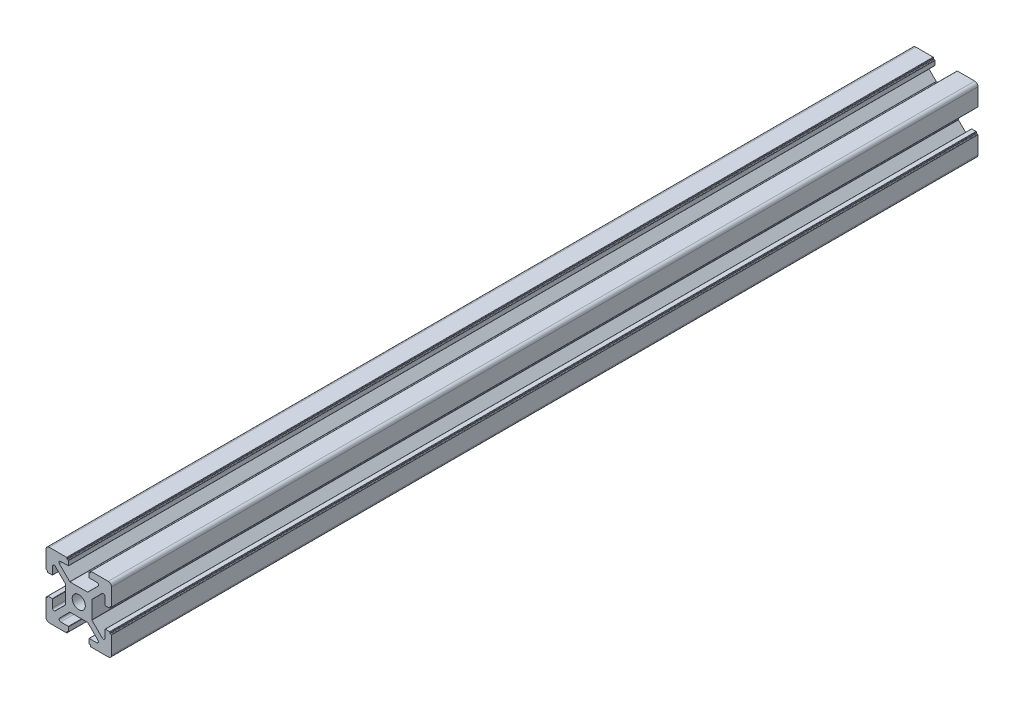
SolidWorks part; units mm, degrees
ref_plane "Plane1" through (0, 0, 0) normal (0, 0, 1) x (1, 0, 0)
ref_plane "Plane2" through (0, 0, 0) normal (0, 1, 0) x (1, 0, 0)
ref_plane "Plane3" through (0, 0, 0) normal (1, 0, 0) x (0, 0, -1)
sketch "Sketch1" plane through (0, 0, 0) normal (0, 0, 1) x (1, 0, 0)
  line L0 (-26.4662, 0) -> (25.1675, 0) construction
  line L1 (0, 16.7588) -> (0, -17.8201) construction
  line L2 (-10, 9) -> (-10, 3.7)
  line L3 (8, -5.5201) -> (8, -3.2)
  line L4 (-4, 0) -> (-4, 2.6858)
  line L5 (-2.6858, 4) -> (2.6858, 4)
  line L6 (4, 0) -> (4, 2.6858)
  line L7 (-4, -4) -> (4, 4) construction
  line L8 (-4, 4) -> (4, -4) construction
  line L9 (-9, 10) -> (-3.7, 10)
  line L10 (-8, 5.5201) -> (-8, 3.2)
  line L11 (10, -9) -> (10, -3.7)
  line L12 (9.6, -3.6) -> (9.9, -3.6)
  line L13 (-10, 10) -> (10, -10) construction
  line L14 (-10, -10) -> (10, 10) construction
  line L15 (9.5, -3.2) -> (9.5, -3.5)
  line L16 (8.1, -3.1) -> (9.4, -3.1)
  line L17 (-5.5201, 8) -> (-3.2, 8)
  line L18 (-7.1464, 5.8737) -> (-4.0293, 2.7565)
  line L19 (-5.8737, 7.1464) -> (-2.7565, 4.0293)
  line L20 (-3.1, 8.1) -> (-3.1, 9.4)
  line L21 (-3.2, 9.5) -> (-3.5, 9.5)
  line L22 (-3.6, 9.6) -> (-3.6, 9.9)
  line L23 (3.1, 8.1) -> (3.1, 9.4)
  line L24 (3.2, 9.5) -> (3.5, 9.5)
  line L25 (3.6, 9.6) -> (3.6, 9.9)
  line L26 (2.7565, 4.0293) -> (5.8737, 7.1464)
  line L27 (4.0293, 2.7565) -> (7.1464, 5.8737)
  line L28 (-8, 8) -> (8, 8) construction
  line L29 (-8, 8) -> (-8, -8) construction
  line L30 (8, 8) -> (8, -8) construction
  line L31 (3.7, 10) -> (9, 10)
  line L32 (-9, 10) -> (9, 10) construction
  line L33 (3.2, 8) -> (5.5201, 8)
  line L34 (-9.5, 3.2) -> (-9.5, 3.5)
  line L35 (-9.6, 3.6) -> (-9.9, 3.6)
  line L36 (-8.1, 3.1) -> (-9.4, 3.1)
  line L37 (-9, -10) -> (9, -10) construction
  line L38 (-10, 9) -> (-10, -9) construction
  line L39 (-8, -8) -> (8, -8) construction
  line L40 (10, 9) -> (10, -9) construction
  line L41 (8.1, 3.1) -> (9.4, 3.1)
  line L42 (9.5, 3.2) -> (9.5, 3.5)
  line L43 (9.6, 3.6) -> (9.9, 3.6)
  line L44 (10, 9) -> (10, 3.7)
  line L45 (8, 5.5201) -> (8, 3.2)
  line L46 (-8.1, -3.1) -> (-9.4, -3.1)
  line L47 (-9.6, -3.6) -> (-9.9, -3.6)
  line L48 (-9.5, -3.2) -> (-9.5, -3.5)
  line L49 (3.2, -8) -> (5.5201, -8)
  line L50 (3.7, -10) -> (9, -10)
  line L51 (4.0293, -2.7565) -> (7.1464, -5.8737)
  line L52 (2.7565, -4.0293) -> (5.8737, -7.1464)
  line L53 (3.6, -9.6) -> (3.6, -9.9)
  line L54 (3.2, -9.5) -> (3.5, -9.5)
  line L55 (3.1, -8.1) -> (3.1, -9.4)
  line L56 (-3.6, -9.6) -> (-3.6, -9.9)
  line L57 (-3.2, -9.5) -> (-3.5, -9.5)
  line L58 (-3.1, -8.1) -> (-3.1, -9.4)
  line L59 (-5.8737, -7.1464) -> (-2.7565, -4.0293)
  line L60 (-7.1464, -5.8737) -> (-4.0293, -2.7565)
  line L61 (-5.5201, -8) -> (-3.2, -8)
  line L62 (-8, -5.5201) -> (-8, -3.2)
  line L63 (-9, -10) -> (-3.7, -10)
  line L64 (-2.6858, -4) -> (2.6858, -4)
  line L65 (-10, -9) -> (-10, -3.7)
  line L66 (-4, 0) -> (-4, -2.6858)
  line L68 (4, 0) -> (4, -2.6858)
  circle A0 centre (0, 0) radius 2
  arc A1 (-10, 9) -> (-9, 10) centre (-9, 9) cw
  arc A2 (10, -3.7) -> (9.9, -3.6) centre (9.9, -3.7) ccw
  arc A3 (-10, -9) -> (-9, -10) centre (-9, -9) ccw construction
  arc A4 (10, 9) -> (9, 10) centre (9, 9) ccw
  arc A5 (-8, -8) -> (-8, -8) centre (-8, -8) ccw
  arc A6 (8, -8) -> (8, -8) centre (8, -8) cw
  arc A7 (8, 8) -> (8, 8) centre (8, 8) ccw
  arc A8 (-8, 8) -> (-8, 8) centre (-8, 8) cw
  arc A9 (-5.5201, 8) -> (-5.8737, 7.1464) centre (-5.5201, 7.5) ccw
  arc A10 (5.5201, 8) -> (5.8737, 7.1464) centre (5.5201, 7.5) cw
  arc A11 (-8, 5.5201) -> (-7.1464, 5.8737) centre (-7.5, 5.5201) cw
  arc A12 (8, 5.5201) -> (7.1464, 5.8737) centre (7.5, 5.5201) ccw
  arc A13 (-3.6, 9.9) -> (-3.7, 10) centre (-3.7, 9.9) ccw
  arc A14 (-3.5, 9.5) -> (-3.6, 9.6) centre (-3.5, 9.6) cw
  arc A15 (-3.2, 9.5) -> (-3.1, 9.4) centre (-3.2, 9.4) cw
  arc A16 (-3.1, 8.1) -> (-3.2, 8) centre (-3.2, 8.1) cw
  arc A17 (3.2, 8) -> (3.1, 8.1) centre (3.2, 8.1) cw
  arc A18 (3.2, 9.5) -> (3.1, 9.4) centre (3.2, 9.4) ccw
  arc A19 (3.5, 9.5) -> (3.6, 9.6) centre (3.5, 9.6) ccw
  arc A20 (3.7, 10) -> (3.6, 9.9) centre (3.7, 9.9) ccw
  arc A21 (-2.6858, 4) -> (-2.7565, 4.0293) centre (-2.6858, 4.1) cw
  arc A22 (-4, 2.6858) -> (-4.0293, 2.7565) centre (-4.1, 2.6858) ccw
  arc A23 (2.6858, 4) -> (2.7565, 4.0293) centre (2.6858, 4.1) ccw
  arc A24 (4.0293, 2.7565) -> (4, 2.6858) centre (4.1, 2.6858) ccw
  arc A25 (-9.5, 3.2) -> (-9.4, 3.1) centre (-9.4, 3.2) ccw
  arc A26 (-9.5, 3.5) -> (-9.6, 3.6) centre (-9.6, 3.5) ccw
  arc A27 (-9.9, 3.6) -> (-10, 3.7) centre (-9.9, 3.7) cw
  arc A28 (-8.1, 3.1) -> (-8, 3.2) centre (-8.1, 3.2) ccw
  arc A29 (8, 3.2) -> (8.1, 3.1) centre (8.1, 3.2) ccw
  arc A30 (9.5, 3.2) -> (9.4, 3.1) centre (9.4, 3.2) cw
  arc A31 (9.5, 3.5) -> (9.6, 3.6) centre (9.6, 3.5) cw
  arc A32 (10, 3.7) -> (9.9, 3.6) centre (9.9, 3.7) cw
  arc A33 (10, -9) -> (9, -10) centre (9, -9) cw construction
  arc A34 (9.5, -3.5) -> (9.6, -3.6) centre (9.6, -3.5) ccw
  arc A35 (9.5, -3.2) -> (9.4, -3.1) centre (9.4, -3.2) ccw
  arc A36 (8, -3.2) -> (8.1, -3.1) centre (8.1, -3.2) cw
  arc A37 (-8.1, -3.1) -> (-8, -3.2) centre (-8.1, -3.2) cw
  arc A38 (-9.9, -3.6) -> (-10, -3.7) centre (-9.9, -3.7) ccw
  arc A39 (-9.5, -3.5) -> (-9.6, -3.6) centre (-9.6, -3.5) cw
  arc A40 (-9.5, -3.2) -> (-9.4, -3.1) centre (-9.4, -3.2) cw
  arc A41 (4.0293, -2.7565) -> (4, -2.6858) centre (4.1, -2.6858) cw
  arc A42 (2.6858, -4) -> (2.7565, -4.0293) centre (2.6858, -4.1) cw
  arc A43 (-4, -2.6858) -> (-4.0293, -2.7565) centre (-4.1, -2.6858) cw
  arc A44 (-2.6858, -4) -> (-2.7565, -4.0293) centre (-2.6858, -4.1) ccw
  arc A45 (3.7, -10) -> (3.6, -9.9) centre (3.7, -9.9) cw
  arc A46 (3.5, -9.5) -> (3.6, -9.6) centre (3.5, -9.6) cw
  arc A47 (3.2, -9.5) -> (3.1, -9.4) centre (3.2, -9.4) cw
  arc A48 (3.2, -8) -> (3.1, -8.1) centre (3.2, -8.1) ccw
  arc A49 (-3.1, -8.1) -> (-3.2, -8) centre (-3.2, -8.1) ccw
  arc A50 (-3.2, -9.5) -> (-3.1, -9.4) centre (-3.2, -9.4) ccw
  arc A51 (-3.5, -9.5) -> (-3.6, -9.6) centre (-3.5, -9.6) ccw
  arc A52 (-3.6, -9.9) -> (-3.7, -10) centre (-3.7, -9.9) cw
  arc A53 (8, -5.5201) -> (7.1464, -5.8737) centre (7.5, -5.5201) cw
  arc A54 (-8, -5.5201) -> (-7.1464, -5.8737) centre (-7.5, -5.5201) ccw
  arc A55 (5.5201, -8) -> (5.8737, -7.1464) centre (5.5201, -7.5) ccw
  arc A56 (-5.5201, -8) -> (-5.8737, -7.1464) centre (-5.5201, -7.5) cw
  arc A57 (10, -9) -> (9, -10) centre (9, -9) cw
  arc A58 (-10, -9) -> (-9, -10) centre (-9, -9) ccw
  point P0 (0, 0)
  point P70 (3.1, 8.75)
  point P72 (-3.6, 10)
  point P75 (-3.6, 9.5)
  point P82 (3.1, 8)
  point P87 (3.6, 9.5)
  point P90 (3.6, 10)
  point P198 (3.6, -10)
  point P199 (3.6, -9.5)
  point P200 (3.1, -8)
  point P201 (-3.6, -9.5)
  point P202 (-3.6, -10)
extrude "Boss-Extrude1" add sketch "Sketch1" along normal blind 264.5 contours L65 A58 L63 A52 L56 A51 L57 A50 L58 A49 L61 A56 L59 A44 L64 A42 L52 A55 L49 A48 L55 A47 L54 A46 L53 A45 L50 A57 L11 A2 L12 A34 L15 A35 L16 A36 L3 A53 L51 A41 L68 L6 A24 L27 A12 L45 A29 L41 A30 L42 A31
